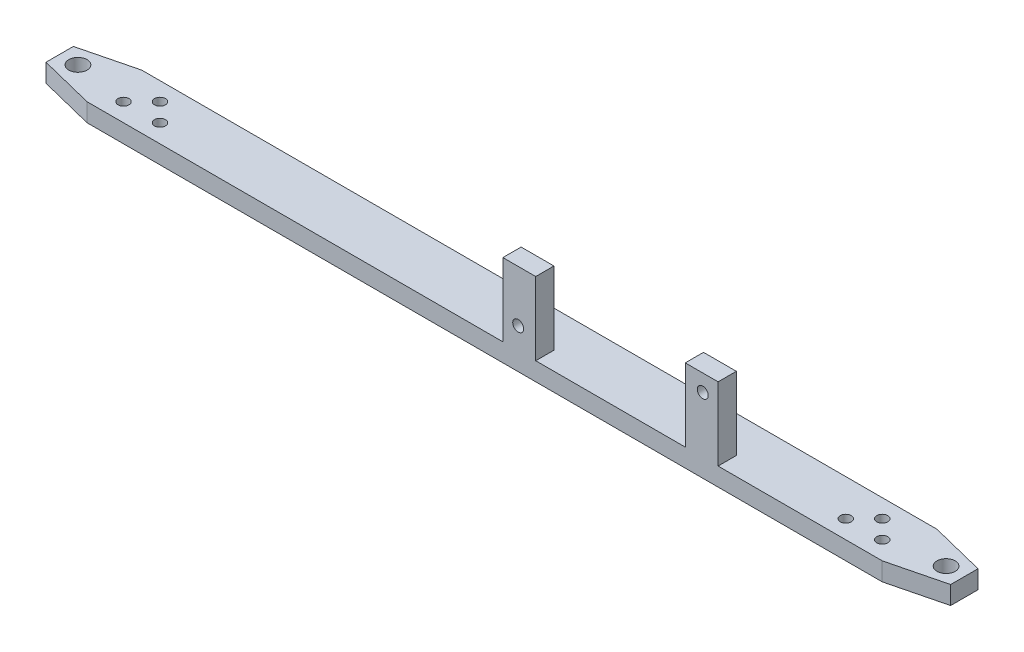
SolidWorks part; units mm, degrees
ref_plane "Front Plane" through (0, 0, 0) normal (0, 0, 1) x (1, 0, 0)
ref_plane "Top Plane" through (0, 0, 0) normal (0, 1, 0) x (1, 0, 0)
ref_plane "Right Plane" through (0, 0, 0) normal (1, 0, 0) x (0, 0, -1)
sketch "Sketch1" plane through (0, 0, 0) normal (0, 1, 0) x (1, 0, 0)
  line L0 (-67.5983, 7.3191) -> (-52.5983, 3.5691)
  line L1 (-52.5983, 3.5691) -> (165.4017, 3.5691)
  line L2 (165.4017, 3.5691) -> (180.4017, 7.3191)
  line L3 (180.4017, 7.3191) -> (180.4017, 14.8191)
  line L4 (180.4017, 14.8191) -> (165.4017, 18.5691)
  line L5 (165.4017, 18.5691) -> (-52.5983, 18.5691)
  line L6 (-52.5983, 18.5691) -> (-67.5983, 14.8191)
  line L7 (-67.5983, 14.8191) -> (-67.5983, 7.3191)
  dimension "D1" = 218
  dimension "D2" = 218
  dimension "D3" = 0
  dimension "D4" = 248
  dimension "D5" = 15
  dimension "D6" = 15
  dimension "D7" = 7.5
  dimension "D8" = 7.5
  dimension "D9" = 3.75
  dimension "D10" = 3.75
extrude "Boss-Extrude1" add sketch "Sketch1" along normal blind 5
sketch "Sketch2" plane through (0, 5, 0) normal (0, 1, 0) x (1, 0, 0)
  line L0 (165.4017, 18.5691) -> (-52.5983, 18.5691) construction
  line L1 (-52.5983, 3.5691) -> (165.4017, 3.5691) construction
  line L2 (180.4017, 7.3191) -> (180.4017, 14.8191) construction
  line L3 (-67.5983, 14.8191) -> (-67.5983, 7.3191) construction
  circle A0 centre (155.4017, 13.5691) radius 1.5
  circle A1 centre (160.4017, 8.5691) radius 1.5
  circle A2 centre (150.4017, 8.5691) radius 1.5
  circle A3 centre (-47.5983, 8.5691) radius 1.5
  circle A4 centre (-37.5983, 8.5691) radius 1.5
  circle A5 centre (-42.5983, 13.5691) radius 1.5
  circle A6 centre (-62.5983, 11.0691) radius 2.5
  circle A7 centre (175.4017, 11.0691) radius 2.5
  point P24 (180.4017, 11.0691)
  point P27 (-67.5983, 11.0691)
  dimension "D1" = 3
  dimension "D2" = 3
  dimension "D3" = 3
  dimension "D4" = 5
  dimension "D5" = 5
  dimension "D6" = 3
  dimension "D7" = 3
  dimension "D8" = 3
  dimension "D9" = 5
  dimension "D10" = 5
  dimension "D11" = 5
  dimension "D12" = 5
  dimension "D13" = 15
  dimension "D14" = 10
  dimension "D15" = 5
  dimension "D16" = 5
  dimension "D17" = 5
  dimension "D18" = 15
  dimension "D19" = 5
  dimension "D20" = 10
  dimension "D21" = 0
  dimension "D22" = 0
  dimension "D23" = 5
  dimension "D24" = 5
extrude "Cut-Extrude1" cut sketch "Sketch2" against normal blind 5
sketch "Sketch4" plane through (-36.6961, 5, 1.6275) normal (0, 1, 0) x (1, 0, 0)
  line L1 (98.0978, 5.1966) -> (107.0978, 5.1966)
  line L2 (98.0978, 5.1966) -> (98.0978, 10.1966)
  line L3 (98.0978, 10.1966) -> (107.0978, 10.1966)
  line L4 (107.0978, 5.1966) -> (107.0978, 10.1966)
  line L5 (-15.9022, 5.1966) -> (202.0978, 5.1966) construction
  line L6 (148.0978, 5.1966) -> (157.0978, 5.1966)
  line L7 (148.0978, 5.1966) -> (148.0978, 10.1966)
  line L8 (148.0978, 10.1966) -> (157.0978, 10.1966)
  line L9 (157.0978, 5.1966) -> (157.0978, 10.1966)
  dimension "D1" = 41
  dimension "D2" = 9
  dimension "D3" = 9
  dimension "D4" = 5
  dimension "D5" = 5
  dimension "D6" = 0
  dimension "D7" = 0
  dimension "D8" = 45
extrude "Boss-Extrude2" add sketch "Sketch4" along normal blind 20
sketch "Sketch6" plane through (-36.6961, 0, -3.5691) normal (0, 0, 1) x (1, 0, 0)
  line L1 (148.0978, 25) -> (148.0978, 5) construction
  line L2 (107.0978, 25) -> (107.0978, 5) construction
  line L4 (148.0978, 25) -> (157.0978, 25) construction
  circle A0 centre (102.2978, 10.9) radius 1.5
  circle A1 centre (152.8978, 20.4) radius 1.5
  dimension "D1" = 3
  dimension "D2" = 3
  dimension "D3" = 4.6
  dimension "D4" = 9.5
  dimension "D5" = 4.8
  dimension "D6" = 4.8
extrude "Cut-Extrude2" cut sketch "Sketch6" against normal blind 5
